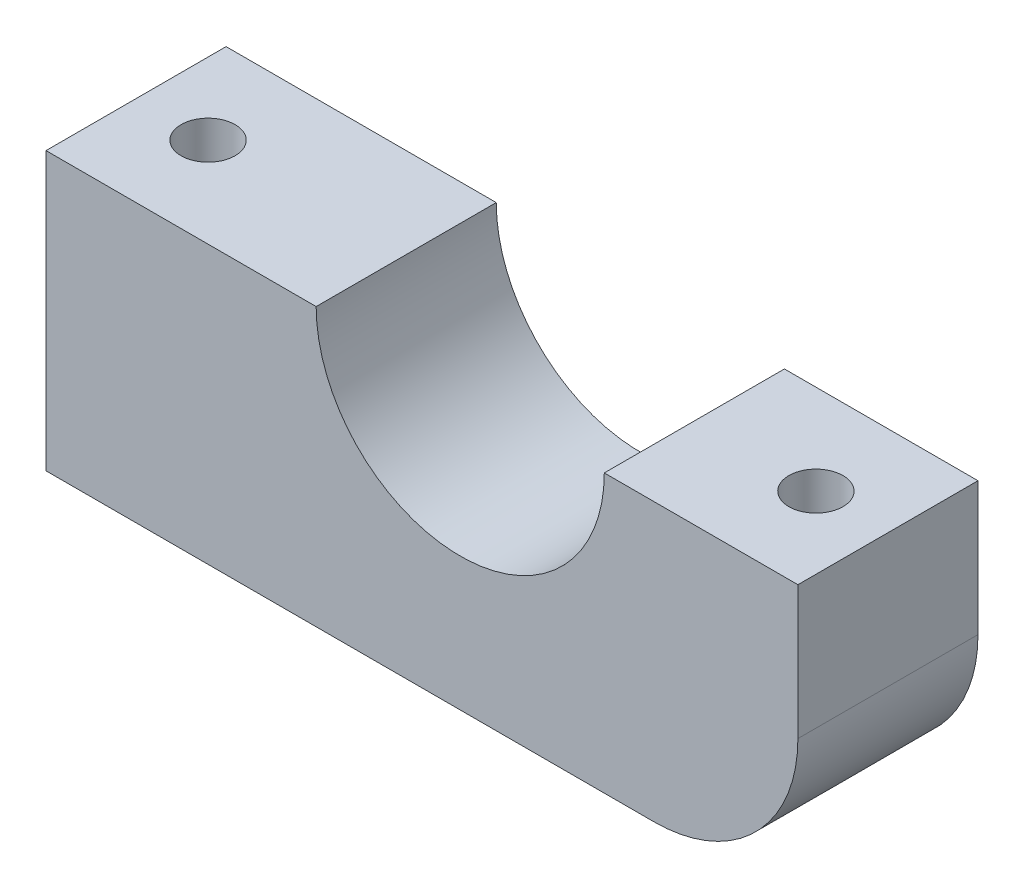
SolidWorks part; units mm, degrees
material "PLA 100% Infill"
ref_plane "Front Plane" through (0, 0, 0) normal (0, 0, 1) x (1, 0, 0)
ref_plane "Top Plane" through (0, 0, 0) normal (0, 1, 0) x (1, 0, 0)
ref_plane "Right Plane" through (0, 0, 0) normal (1, 0, 0) x (0, 0, -1)
sketch "Sketch1" plane through (0, 0, 0) normal (0, 0, 1) x (1, 0, 0)
  line L0 (0, 0) -> (-10.75, 0)
  line L1 (-26.75, 0) -> (-41.75, 0)
  line L2 (-41.75, 0) -> (-41.75, -15.4)
  line L3 (-41.75, -15.4) -> (-8, -15.4)
  line L4 (0, -7.4) -> (0, 0)
  arc A0 (-10.75, 0) -> (-26.75, 0) centre (-18.75, 0) cw
  arc A1 (-8, -15.4) -> (0, -7.4) centre (-8, -7.4) ccw
  dimension "D1" = 8
  dimension "D2" = 10.75
  dimension "D3" = 15
  dimension "D4" = 15.4
  dimension "D5" = 33.75
extrude "Boss-Extrude1" add sketch "Sketch1" along normal blind 10
sketch "Sketch2" plane through (0, -15.4, 0) normal (0, -1, 0) x (1, 0, 0)
  line L0 (-41.75, 5) -> (0, 5) construction
  line L1 (-41.75, 10) -> (-41.75, 0) construction
  line L2 (0, 10) -> (0, 0) construction
  circle A0 centre (-37.75, 5) radius 1.5
  circle A1 centre (-4, 5) radius 1.5
  dimension "D3" = 3
  dimension "D1" = 4
  dimension "D2" = 4
extrude "Cut-Extrude1" cut sketch "Sketch2" against normal through all
